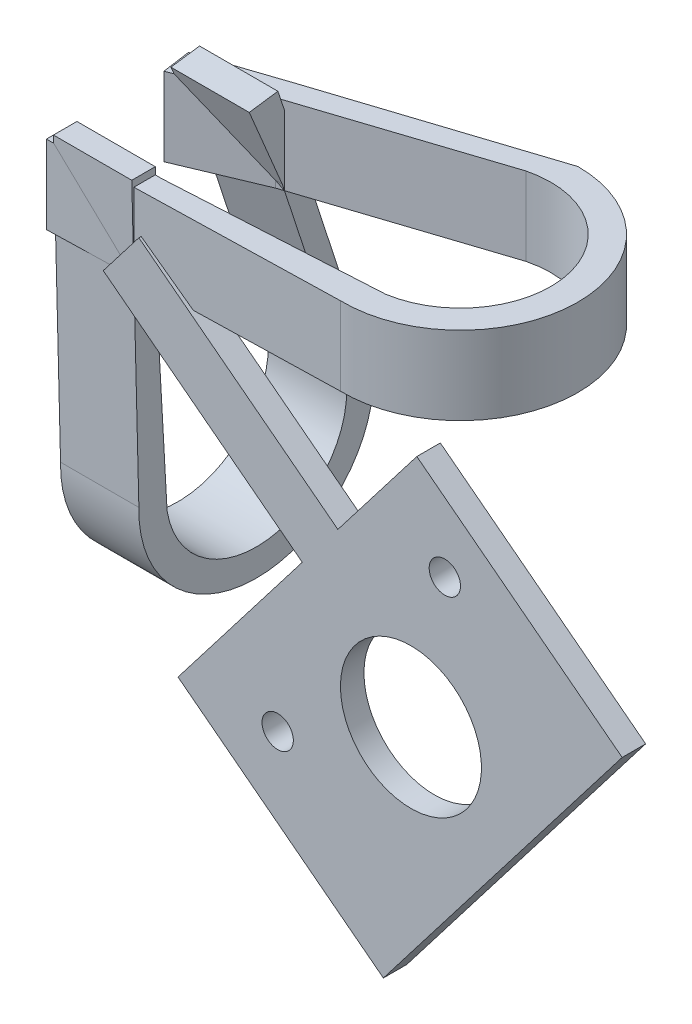
SolidWorks part; units mm, degrees
ref_plane "Front Plane" through (0, 0, 0) normal (0, 0, 1) x (1, 0, 0)
ref_plane "Top Plane" through (0, 0, 0) normal (0, 1, 0) x (1, 0, 0)
ref_plane "Right Plane" through (0, 0, 0) normal (1, 0, 0) x (0, 0, -1)
sketch "Sketch1" plane through (0, 0, 0) normal (0, 1, 0) x (1, 0, 0)
  line L0 (0, 15) -> (-26.9002, 6.2787)
  line L1 (-26.9002, 6.2787) -> (-37.4744, 2.7504)
  line L2 (-36.9587, -0.904) -> (-26.9002, 3.3174)
  line L3 (-0.3257, -14.9965) -> (-36.9587, -15.904)
  line L4 (-36.9587, -15.904) -> (-36.9587, -12.904)
  line L5 (-32.5869, -12.904) -> (-25.1455, -12.904)
  line L6 (-26.9002, 3.3174) -> (-2.8211, 11.1932)
  line L7 (-25.1455, -12.904) -> (1.8518, -11.3937)
  line L8 (-32.5869, -12.904) -> (-36.9587, -12.904)
  line L9 (-37.4744, 2.7504) -> (-36.9587, -0.904)
  arc A0 (-0.3257, -14.9965) -> (0, 15) centre (0, 0) ccw
  arc A1 (1.8518, -11.3937) -> (-2.8211, 11.1932) centre (0, 0) ccw
  point P1 (1.9927, -11.881)
  point P5 (-49.7199, -11.2003)
  point P15 (-32.6102, -11.2003)
  point P17 (-51.0871, 7.636)
  point P18 (-36.9587, 7.282)
  point P19 (-30.915, 3.8917)
  point P20 (-33.3239, 7.3712)
  point P21 (-38.0526, 15)
  point P22 (0, 0)
  point P23 (-36.1484, 0)
  point P24 (-34.2161, 10.2262)
  point P25 (-26.9002, 1.4827)
  point P26 (-26.9002, 6.2787)
  point P27 (-26.9002, 3.3174)
  point P28 (-36.1484, 3.3174)
  point P29 (-34.0721, -2.3531)
  point P30 (-36.9587, -0.904)
  point P31 (-37.4744, 2.7504)
  point P32 (-2.8211, 11.1932)
  point P33 (0, 15)
  point P34 (0, 15)
  point P35 (0, 0)
  point P36 (0, 0)
  dimension "D1" = 30
  dimension "D2" = 12
extrude "Boss-Extrude1" add sketch "Sketch1" along normal blind 10
pattern_circular "CirPattern1" count 2 every 90 about axis through (-31.0521, 5, 0) along (0, 0, 1) of "Boss-Extrude1"
sketch "Sketch3" plane through (-4.5801, 0, -13.7263) normal (-0.3165, 0, -0.9486) x (-0.9486, 0, 0.3165)
sketch "Sketch4" plane through (0, 0, 12.904) normal (0, 0, -1) x (-1, 0, 0)
  line L0 (25.1455, 5) -> (29.6894, -0.9066)
  line L1 (25.1455, 5) -> (-0.2612, -14.5451)
  line L2 (29.6894, -0.9066) -> (4.2826, -20.4517)
  line L4 (25.1455, 10) -> (25.1455, 0) construction
  line L5 (26.0521, -0.9066) -> (36.0521, -0.9066) construction
  line L6 (20.1451, -41.0714) -> (4.2826, -20.4517)
  line L7 (20.1451, -41.0714) -> (-6.0701, -61.2385)
  line L8 (-10.3419, -1.4413) -> (-36.5571, -21.6084)
  line L9 (-6.0701, -61.2385) -> (-36.5571, -21.6084)
  line L10 (-0.2612, -14.5451) -> (-10.3419, -1.4413)
  line L11 (-9.5885, -31.7371) -> (-25.0783, -11.6019) construction
  line L12 (7.4228, -40.7297) -> (1.082, -45.6076) construction
  line L13 (7.4228, -40.7297) -> (-13.9181, -12.9886) construction
  line L14 (-13.9181, -12.9886) -> (7.4228, -40.7297) construction
  line L15 (-9.5885, -31.7371) -> (-3.2477, -26.8591) construction
  line L16 (-13.9181, -12.9886) -> (-32.3061, -27.1343)
  circle A0 centre (-13.9181, -12.9886) radius 2
  circle A1 centre (7.4228, -40.7297) radius 2
  circle A2 centre (-9.5885, -31.7371) radius 9
  dimension "D2" = 4
  dimension "D3" = 4
  dimension "D5" = 18
  dimension "D6" = 8
  dimension "D7" = 17.5
  dimension "D1" = 50
  dimension "D4" = 35
extrude "Boss-Extrude2" add sketch "Sketch4" against normal blind 3 contours L6 L2 L0 L1 L10 L8 L9 L7 | A2 | A1 | A0
